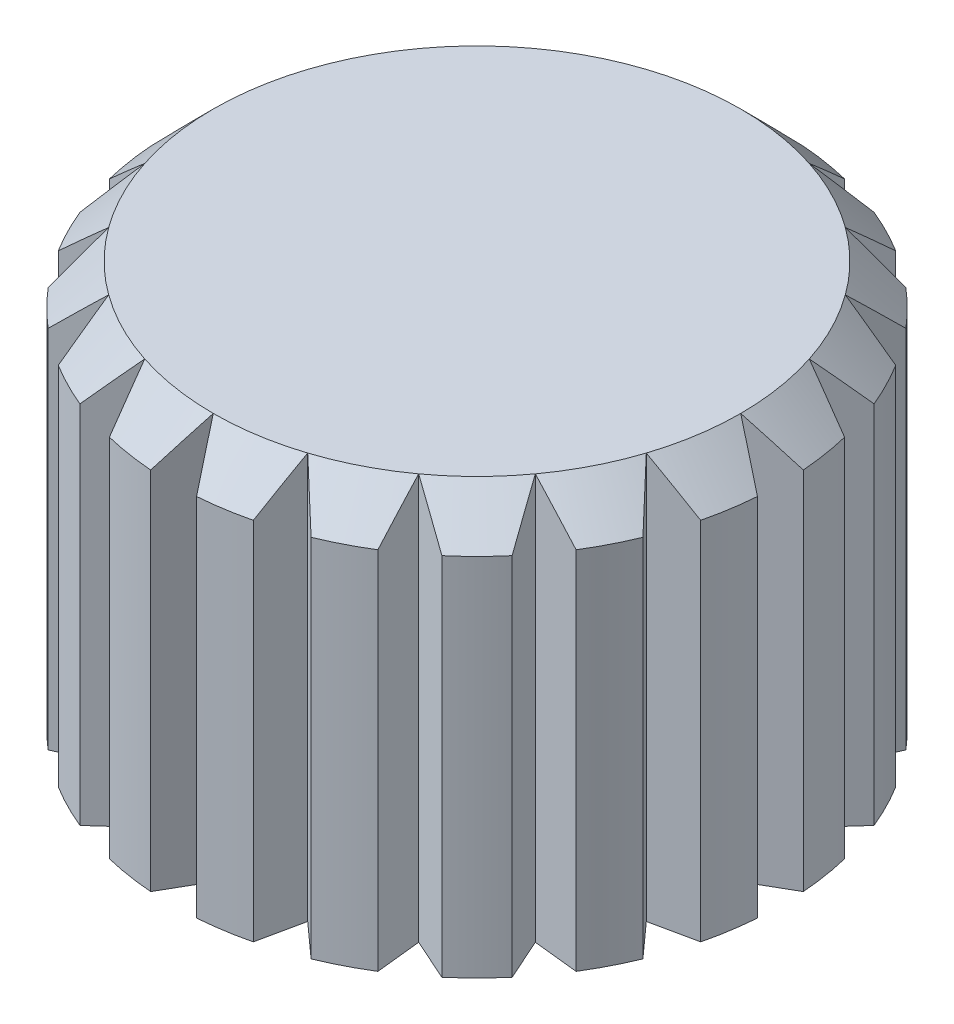
SolidWorks part; units mm, degrees
ref_plane "Ebene vorne" through (0, 0, 0) normal (0, 0, 1) x (1, 0, 0)
ref_plane "Ebene oben" through (0, 0, 0) normal (0, 1, 0) x (1, 0, 0)
ref_plane "Ebene rechts" through (0, 0, 0) normal (1, 0, 0) x (0, 0, -1)
sketch "Sketch1" plane through (0, 0, 0) normal (0, 0, 1) x (1, 0, 0)
  line L0 (0, 0) -> (0, 10) construction
  line L1 (0, 8) -> (0, 10)
  line L2 (0, 10) -> (7.5, 10)
  line L3 (7.5, 10) -> (7.5, 0)
  line L4 (7.5, 0) -> (4, 0)
  line L5 (3.05, 5) -> (3.05, 8)
  line L6 (3.05, 8) -> (0, 8)
  line L7 (3.05, 5) -> (4, 5)
  line L8 (4, 5) -> (4, 0)
  dimension "D1" = 10
  dimension "D2" = 6.1
  dimension "D3" = 15
  dimension "D4" = 8
  dimension "D5" = 8
  dimension "D6" = 5
revolve "Revolve1" add sketch "Sketch1" angle 360 about L0
sketch "Sketch2" plane through (0, 10, 0) normal (0, 1, 0) x (1, 0, 0)
  line L0 (0, 8.5) -> (1.1547, 8.5)
  line L1 (1.1547, 8.5) -> (0, 6.5)
  line L2 (0, 6.5) -> (-1.1547, 8.5)
  line L3 (-1.1547, 8.5) -> (0, 8.5)
  line L4 (0, 0) -> (0, 8.5) construction
  circle A0 centre (0, 0) radius 7.5 construction
  point P2 (0, 7.5)
  point P7 (0, 7.5)
  dimension "D1" = 1
  dimension "D2" = 2
  dimension "D3" = 60
extrude "Cut-Extrude1" cut sketch "Sketch2" against normal blind 10
pattern_circular "CirPattern1" count 20 over 360 about axis through (0, 0, 0) along (0, 1, 0) of "Cut-Extrude1"
sketch "Sketch3" plane through (0, 0, 0) normal (0, 0, 1) x (1, 0, 0)
  line L0 (-8, 8.5) -> (-6, 10.5)
  line L1 (-6, 10.5) -> (-8, 10.5)
  line L2 (-8, 10.5) -> (-8, 8.5)
  line L3 (0, 0) -> (0, 9.9424) construction
  dimension "D1" = 8
  dimension "D2" = 10.5
  dimension "D3" = 2
revolve "Cut-Revolve1" cut sketch "Sketch3" angle 360 about L3
